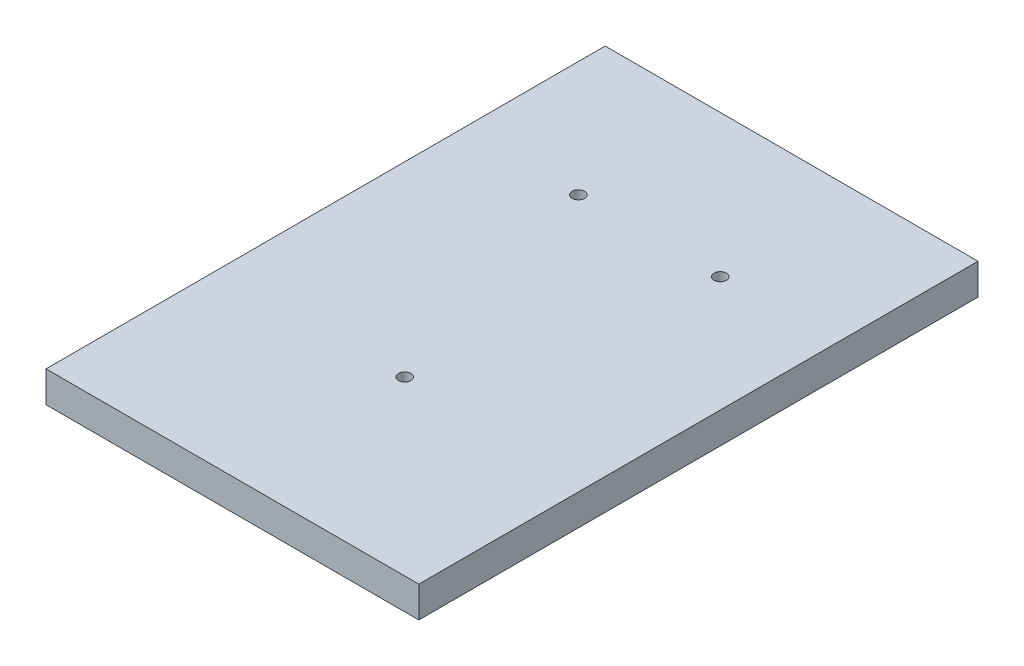
SolidWorks part; units mm, degrees
ref_plane "Front Plane" through (0, 0, 0) normal (0, 0, 1) x (1, 0, 0)
ref_plane "Top Plane" through (0, 0, 0) normal (0, 1, 0) x (1, 0, 0)
ref_plane "Right Plane" through (0, 0, 0) normal (1, 0, 0) x (0, 0, -1)
sketch "Sketch1" plane through (0, 0, 0) normal (0, 1, 0) x (1, 0, 0)
  line L0 (0, -57.15) -> (0, 57.15) construction
  line L1 (-38.1, -57.15) -> (38.1, -57.15)
  line L2 (-38.1, -57.15) -> (-38.1, 57.15)
  line L3 (-38.1, 57.15) -> (38.1, 57.15)
  line L4 (38.1, -57.15) -> (38.1, 57.15)
  line L5 (-38.1, -57.15) -> (38.1, 57.15) construction
  line L6 (-38.1, 57.15) -> (38.1, -57.15) construction
  circle A0 centre (-14.5, 28.0703) radius 1.27
  circle A1 centre (14.5, 28.0703) radius 1.27
  circle A2 centre (0, -21.9297) radius 1.27
  point P0 (0, 0)
  dimension "D1" = 2.54
  dimension "D2" = 76.2
  dimension "D3" = 114.3
  dimension "D4" = 29
  dimension "D5" = 50
extrude "Boss-Extrude1" add sketch "Sketch1" along normal blind 6.35
